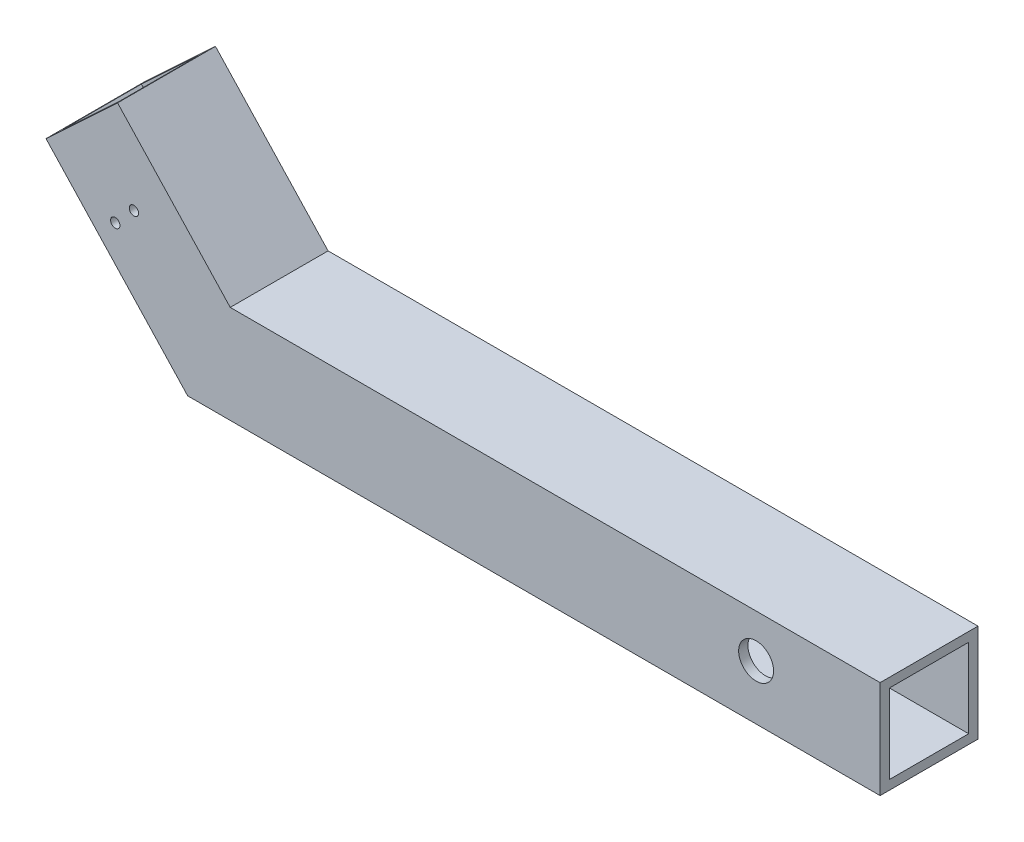
SolidWorks part; units mm, degrees
material "Plain Carbon Steel"
ref_plane "Front Plane" through (0, 0, 0) normal (0, 0, 1) x (1, 0, 0)
ref_plane "Top Plane" through (0, 0, 0) normal (0, 1, 0) x (1, 0, 0)
ref_plane "Right Plane" through (0, 0, 0) normal (1, 0, 0) x (0, 0, -1)
sketch "Sketch1" plane through (0, 0, 0) normal (0, 0, 1) x (1, 0, 0)
  line L0 (0, 0) -> (-171.8358, 0)
  line L1 (-190.4121, 8.0772) -> (-217.5255, 37.1528)
  line L2 (-171.8358, 0) -> (-182.88, 0)
  line L3 (-190.4121, 8.0772) -> (-182.88, 0)
  point P6 (-182.88, 0)
  dimension "D1" = 182.88
  dimension "D2" = 50.8
  dimension "D3" = 133
sketch "Sketch2" plane through (0, 0, 0) normal (1, 0, 0) x (0, 0, -1)
  line L0 (-13.335, 13.335) -> (13.335, 13.335)
  line L1 (-10.795, -10.795) -> (10.795, -10.795)
  line L2 (-10.795, -10.795) -> (-10.795, 10.795)
  line L3 (-10.795, 10.795) -> (10.795, 10.795)
  line L4 (10.795, -10.795) -> (10.795, 10.795)
  line L5 (-10.795, -10.795) -> (10.795, 10.795) construction
  line L6 (-10.795, 10.795) -> (10.795, -10.795) construction
  line L7 (13.335, -13.335) -> (13.335, 13.335)
  line L8 (-13.335, -13.335) -> (13.335, -13.335)
  line L9 (-13.335, -13.335) -> (-13.335, 13.335)
  point P0 (0, 0)
  dimension "D1" = 21.59
  dimension "D2" = 2.54
sweep "Sweep1" add profiles "Sketch2" path "Sketch1"
sketch "Sketch3" plane through (-119.707, 128.37, 0) normal (-0.682, 0.7314, 0) x (0.7314, 0.682, 0)
  line L0 (-147.085, -13.335) -> (-147.085, 13.335) construction
  line L1 (-144.545, -10.795) -> (-147.085, -10.795)
  line L2 (-144.545, -10.795) -> (-144.545, 10.795)
  line L3 (-144.545, 10.795) -> (-147.085, 10.795)
  line L4 (-147.085, -10.795) -> (-147.085, 10.795)
sketch "Sketch4" plane through (0, 0, 13.335) normal (0, 0, 1) x (1, 0, 0)
  circle A0 centre (-33.7886, 1.5534) radius 4.7625
extrude "Cut-Extrude2" cut sketch "Sketch4" against normal through all
sketch "Sketch5" plane through (0, 0, 13.335) normal (0, 0, 1) x (1, 0, 0)
  circle A0 centre (-203.3261, 23.0386) radius 1.27
  circle A1 centre (-208.4119, 17.6284) radius 1.27
extrude "Cut-Extrude3" cut sketch "Sketch5" against normal through all
sketch "Sketch6" plane through (0, 0, 13.335) normal (0, 0, 1) x (1, 0, 0)
  circle A0 centre (-78.105, -6.985) radius 2.3622
  circle A1 centre (-88.265, -6.985) radius 2.3622
  circle A2 centre (-33.7886, 1.5534) radius 4.7625
